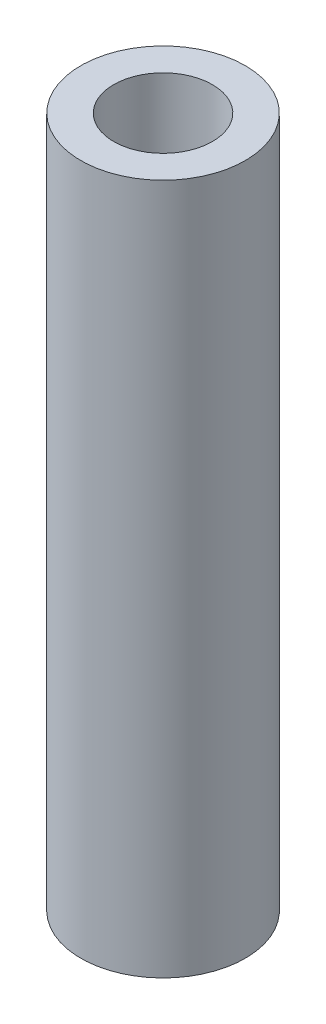
SolidWorks part; units mm, degrees
material "ABS"
ref_plane "Front Plane" through (0, 0, 0) normal (0, 0, 1) x (1, 0, 0)
ref_plane "Top Plane" through (0, 0, 0) normal (0, 1, 0) x (1, 0, 0)
ref_plane "Right Plane" through (0, 0, 0) normal (1, 0, 0) x (0, 0, -1)
sketch "Sketch1" plane through (0, 0, 0) normal (0, 1, 0) x (1, 0, 0)
  circle A0 centre (0, 0) radius 1.5
  circle A1 centre (0, 0) radius 2.5
  dimension "D1" = 3
  dimension "D2" = 5
extrude "Boss-Extrude1" add sketch "Sketch1" along normal blind 21
